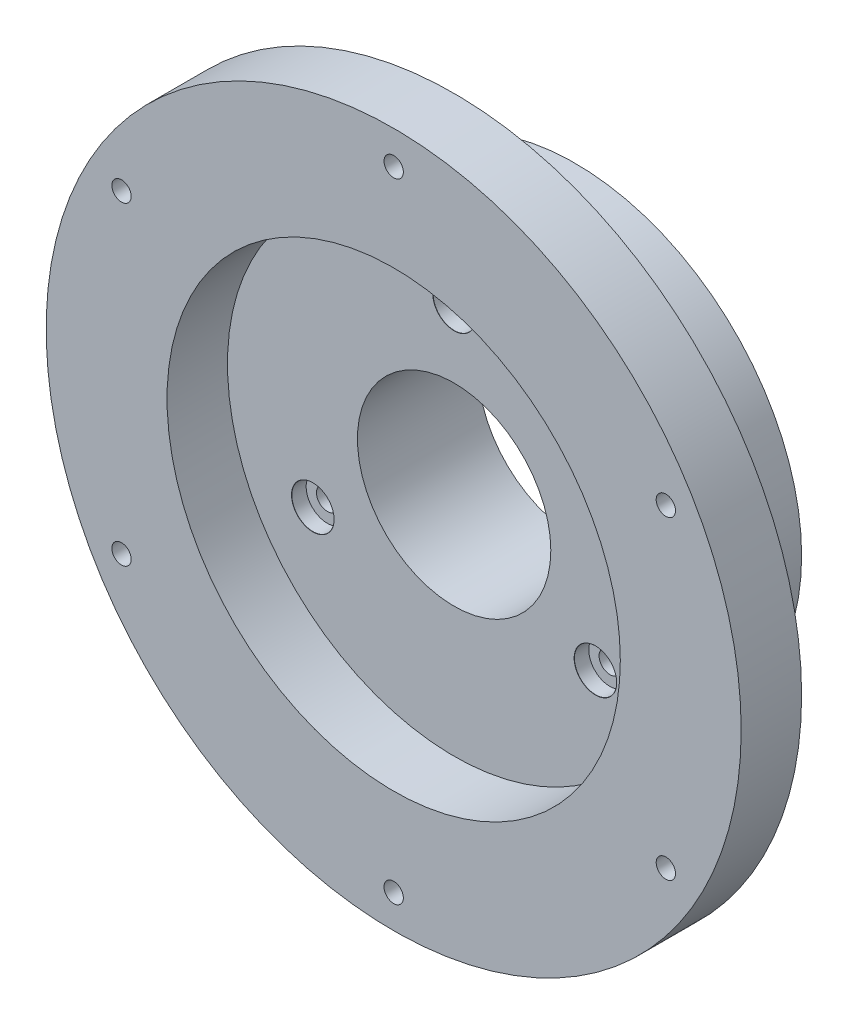
SolidWorks part; units mm, degrees
ref_plane "Front Plane" through (0, 0, 0) normal (0, 0, 1) x (1, 0, 0)
ref_plane "Top Plane" through (0, 0, 0) normal (0, 1, 0) x (1, 0, 0)
ref_plane "Right Plane" through (0, 0, 0) normal (1, 0, 0) x (0, 0, -1)
sketch "Sketch1" plane through (0, 0, 0) normal (0, 0, 1) x (1, 0, 0)
  circle A0 centre (0, 0) radius 37.5
  circle A1 centre (0, 0) radius 16
  point P13 (0, 0)
  dimension "D1" = 75
  dimension "D2" = 32
extrude "Boss-Extrude1" add sketch "Sketch1" along normal blind 20
hole_wizard "CBORE for M3 Pan Head Machine Screw1" positions "Sketch4" profile "Sketch3" counterbore size "M3" standard "ANSI Metric" end condition through all
sketch "Sketch4" plane through (0, 0, 20) normal (0, 0, 1) x (1, 0, 0)
  line L0 (0, 33.4088) -> (0, 0) construction
  line L1 (0, 0) -> (-28.3373, -16.3606) construction
  line L3 (0, 0) -> (27.7898, -16.0445) construction
  point P0 (0, 27)
  point P4 (-23.3827, -13.5)
  point P6 (23.3827, -13.5)
  point P22 (0, 0)
  point P23 (0, 0)
  dimension "D1" = 27
  dimension "D2" = 27
  dimension "D3" = 27
  dimension "D4" = 120
  dimension "D5" = 120
sketch "Sketch3" plane through (0, 27, 20) normal (1, 0, 0) x (0, -1, 0)
  line L0 (0, 0) -> (0, 20)
  line L1 (0, 20) -> (1.8, 20)
  line L3 (1.8, 20) -> (1.8, 2.4)
  line L4 (3.5, 2.4) -> (1.8, 2.4)
  line L5 (3.5, 2.4) -> (3.5, 0.025)
  line L6 (3.5, 0.025) -> (3.525, 0)
  line L7 (3.525, 0) -> (0, 0)
  line L8 (-3.5, 0.025) -> (-3.525, 0) construction
  line L11 (0, -6.35) -> (0, 107.95) construction
  dimension "Thru Hole Dia." = 3.6
  dimension "Thru Hole Depth" = 20
  dimension "C'Bore Dia." = 7
  dimension "C'Bore Depth" = 2.4
  dimension "Near C'Sink Dia." = 7.05
  dimension "Near C'Sink Angle" = 90
ref_plane "Plane1" through (0, 0, 30) normal (0, 0, 1) x (1, 0, 0)
sketch "Sketch8" plane through (0, 0, 30) normal (0, 0, 1) x (1, 0, 0)
  circle A0 centre (0, 0) radius 57.5
  circle A1 centre (0, 0) radius 37.5
  dimension "D1" = 115
extrude "Boss-Extrude3" add sketch "Sketch8" against normal up to surface (10 mm away) separate body up to face at (3.525, 27, 20)
sketch "Sketch9" plane through (0, 0, 30) normal (0, 0, 1) x (1, 0, 0)
  circle A0 centre (0, 0) radius 52 construction
  circle A1 centre (0, 52) radius 1.6
  circle A2 centre (45.0333, 26) radius 1.6
  circle A3 centre (45.0333, -26) radius 1.6
  circle A4 centre (0, -52) radius 1.6
  circle A5 centre (-45.0333, -26) radius 1.6
  circle A6 centre (-45.0333, 26) radius 1.6
  point P17 (0, 0)
  dimension "D1" = 104
  dimension "D2" = 3.2
  dimension "D3" = 6
extrude "Cut-Extrude1" cut sketch "Sketch9" against normal through all
